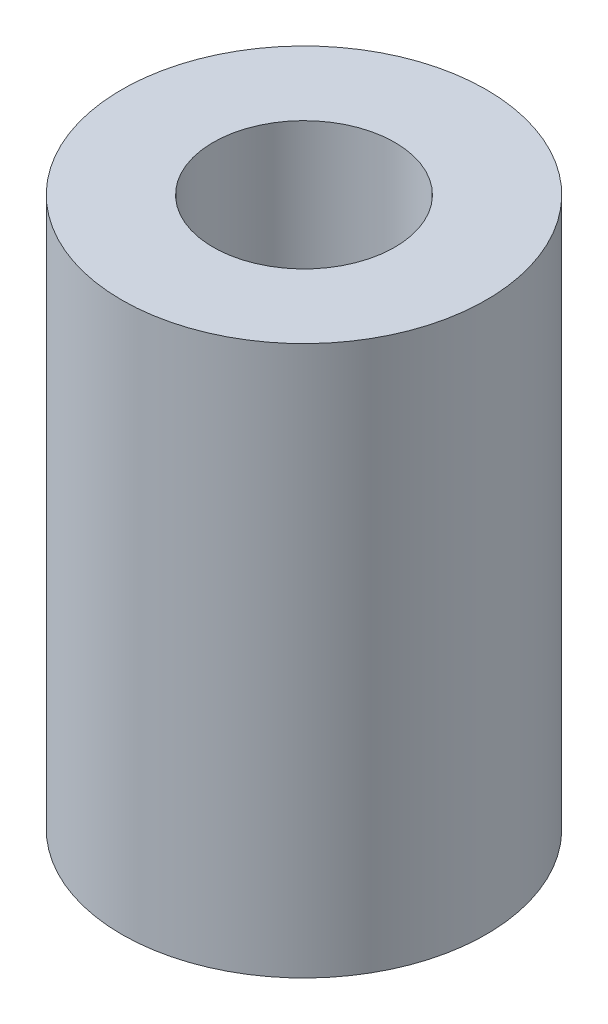
SolidWorks part; units mm, degrees
ref_plane "Front Plane" through (0, 0, 0) normal (0, 0, 1) x (1, 0, 0)
ref_plane "Top Plane" through (0, 0, 0) normal (0, 1, 0) x (1, 0, 0)
ref_plane "Right Plane" through (0, 0, 0) normal (1, 0, 0) x (0, 0, -1)
ref_plane "Plane1"
sketch "Sketch1" plane through (0, 0, 0) normal (0, 1, 0) x (-1, 0, 0)
  circle A0 centre (0, 0) radius 6.32
  circle A1 centre (0, 0) radius 3.15
extrude "Extrusion1" add sketch "Sketch1" along normal blind 19.05 contours A0 A1
